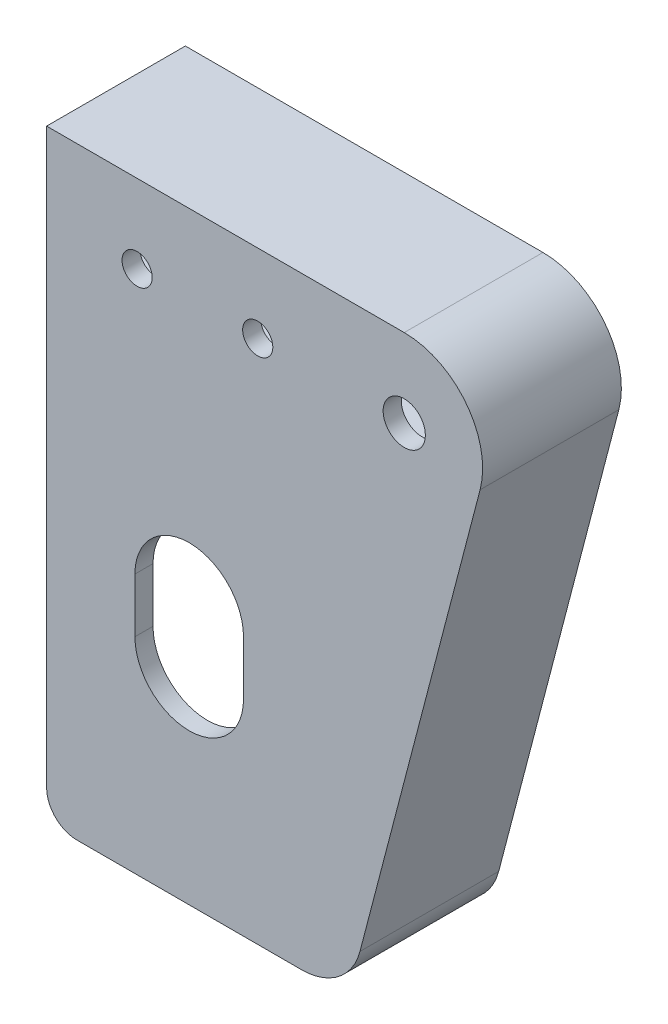
SolidWorks part; units mm, degrees
ref_plane "Front Plane" through (0, 0, 0) normal (0, 0, 1) x (1, 0, 0)
ref_plane "Top Plane" through (0, 0, 0) normal (0, 1, 0) x (1, 0, 0)
ref_plane "Right Plane" through (0, 0, 0) normal (1, 0, 0) x (0, 0, -1)
sketch "Sketch1" plane through (0, 0, 0) normal (0, 0, 1) x (1, 0, 0)
  line L1 (-35, 10) -> (24.2897, 10)
  line L2 (-35, 10) -> (-35, -16)
  line L3 (-35, -16) -> (24.2897, -16)
  line L5 (-35, 10) -> (35.2063, -10.0589) construction
  line L6 (-35, -16) -> (20.8786, 9.5445) construction
  arc A0 (24.2897, -16) -> (24.2897, 10) centre (24.2897, -3) ccw
  point P0 (0, 0)
  dimension "D1" = 26
extrude "Boss-Extrude1" add sketch "Sketch1" against normal blind 3
sketch "Sketch2" plane through (0, 0, -3) normal (0, 0, -1) x (-1, 0, 0)
  line L0 (-24.2897, 7) -> (35, 7)
  line L1 (-24.2897, -13) -> (35, -13)
  line L2 (35, 7) -> (35, 10)
  line L3 (35, -16) -> (35, 10)
  line L4 (35, 10) -> (-24.2897, 10)
  line L5 (-24.2897, -16) -> (35, -16)
  line L6 (35, -16) -> (35, -13)
  line L7 (35, 10) -> (-24.2897, 10)
  line L8 (-24.2897, -16) -> (35, -16)
  arc A0 (-24.2897, 7) -> (-24.2897, -13) centre (-24.2897, -3) ccw
  arc A1 (-24.2897, 10) -> (-24.2897, -16) centre (-24.2897, -3) ccw
  arc A2 (-24.2897, 10) -> (-24.2897, -16) centre (-24.2897, -3) ccw
  dimension "D1" = 0
  dimension "D2" = 3
extrude "Boss-Extrude2" add sketch "Sketch2" along normal blind 20
sketch "Sketch3" plane through (0, 0, 0) normal (0, 0, 1) x (1, 0, 0)
  circle A0 centre (24.2897, -3) radius 3.5
  dimension "D1" = 7
extrude "Cut-Extrude1" cut sketch "Sketch3" against normal blind 20
sketch "Sketch4" plane through (0, 0, 0) normal (0, 0, 1) x (1, 0, 0)
  line L0 (-35, 10) -> (-35, -90)
  line L1 (-35, -90) -> (15, -90)
  line L3 (-35, 10) -> (-35, -16)
  line L4 (-35, -16) -> (24.2897, -16)
  line L5 (24.2897, 10) -> (-35, 10)
  line L7 (-35, -16) -> (24.2897, -16)
  line L8 (24.2897, 10) -> (-35, 10)
  line L9 (15, -90) -> (36.8676, -6.2856)
  arc A1 (24.2897, -16) -> (24.2897, 10) centre (24.2897, -3) ccw
  arc A2 (24.2897, -16) -> (24.2897, 10) centre (24.2897, -3) ccw
  line M10 (-35, -16) -> (24.2897, -16)
  arc M11 (24.2897, -16) -> (24.2897, 10) centre (24.2897, -3) ccw
  dimension "D2" = 50
  dimension "D3" = 100
  dimension "D1" = 0
extrude "Boss-Extrude3" add sketch "Sketch4" against normal blind 3 contours L1 L9 L0 M11 M10
fillet "Fillet1" radius 10 1 edges at (15, -90, -1.5)
fillet "Fillet3" radius 5 1 edges at (-35, -90, -1.5)
sketch "Sketch5" plane through (0, 0, -3) normal (0, 0, -1) x (-1, 0, 0)
  line L8 (-31.8656, -13.5643) -> (-14.0494, -81.7692)
  line L9 (-7.2766, -87) -> (30, -87)
  line L10 (30, -87) -> (30, -90)
  line L11 (-33.965, -5.5274) -> (-14.0494, -81.7692) construction
  line L12 (-7.2766, -90) -> (30, -90)
  line L13 (35, -85) -> (35, -16)
  line L14 (35, -16) -> (-24.2897, -16)
  line L15 (-36.8676, -6.2856) -> (-16.952, -82.5274)
  line L16 (-7.2766, -90) -> (30, -90)
  line L17 (35, -85) -> (35, -16)
  line L18 (35, -16) -> (-24.2897, -16)
  line L19 (-36.8676, -6.2856) -> (-16.952, -82.5274)
  arc A6 (-14.0494, -81.7692) -> (-7.2766, -87) centre (-7.2766, -80) ccw
  arc A9 (30, -90) -> (35, -85) centre (30, -85) ccw
  arc A10 (-36.8676, -6.2856) -> (-24.2897, -16) centre (-24.2897, -3) ccw
  arc A11 (-16.952, -82.5274) -> (-7.2766, -90) centre (-7.2766, -80) ccw
  arc A12 (30, -90) -> (35, -85) centre (30, -85) ccw
  arc A13 (-36.8676, -6.2856) -> (-24.2897, -16) centre (-24.2897, -3) ccw
  arc A14 (-16.952, -82.5274) -> (-7.2766, -90) centre (-7.2766, -80) ccw
  line M12 (-7.2766, -90) -> (30, -90)
  arc M16 (-24.2897, -16) -> (-36.8676, -6.2856) centre (-24.2897, -3) cw
  line M17 (-36.8676, -6.2856) -> (-16.952, -82.5274)
  arc M18 (-16.952, -82.5274) -> (-7.2766, -90) centre (-7.2766, -80) ccw
  dimension "D1" = 0
  dimension "D2" = 3
extrude "Boss-Extrude4" add sketch "Sketch5" along normal blind 20 contours A6 L8 L10 L9 M16 M17 M18 M12
sketch "Sketch6" plane through (0, 0, -3) normal (0, 0, -1) x (-1, 0, 0)
  line L0 (11.3617, -87) -> (11.3617, -16) construction
  line L1 (-45.4177, -38) -> (42.1533, -38) construction
  line L4 (-11.8139, -65) -> (42.1533, -65) construction
  line L5 (-31.8656, -13.5643) -> (-14.0494, -81.7692)
  line L6 (-7.2766, -87) -> (30, -87)
  line L7 (30, -87) -> (30, -90)
  line L8 (35, -85) -> (35, -16)
  line L9 (35, -16) -> (-24.2897, -16)
  line L10 (-31.8656, -13.5643) -> (-14.0494, -81.7692)
  line L11 (-7.2766, -87) -> (30, -87)
  line L12 (30, -87) -> (30, -90)
  line L13 (35, -85) -> (35, -38)
  line L14 (35, -16) -> (-24.2897, -16)
  line L15 (-45.4177, -47) -> (42.1533, -47) construction
  line L16 (-11.8139, -56) -> (42.1533, -56) construction
  line L17 (11.3617, -56) -> (11.3617, -47) construction
  line L18 (2.3617, -56) -> (2.3617, -47)
  line L19 (20.3617, -56) -> (20.3617, -47)
  line L20 (26.9175, -30.7663) -> (26.9175, -70.6479) construction
  arc A2 (2.3617, -56) -> (20.3617, -56) centre (11.3617, -56) ccw
  arc A3 (-31.8656, -13.5643) -> (-24.2897, -16) centre (-24.2897, -3) ccw
  arc A4 (-14.0494, -81.7692) -> (-7.2766, -87) centre (-7.2766, -80) ccw
  arc A5 (30, -90) -> (35, -85) centre (30, -85) ccw
  arc A6 (-31.8656, -13.5643) -> (-24.2897, -16) centre (-24.2897, -3) ccw
  arc A7 (-14.0494, -81.7692) -> (-7.2766, -87) centre (-7.2766, -80) ccw
  arc A8 (30, -90) -> (35, -85) centre (30, -85) ccw
  arc A9 (20.3617, -47) -> (2.3617, -47) centre (11.3617, -47) ccw
  point P23 (11.3617, -51.5)
  dimension "D2" = 22
  dimension "D6" = 9
  dimension "D3" = 9
  dimension "D4" = 22
  dimension "D1" = 0
  dimension "D5" = 9
sketch "Sketch7" plane through (0, 0, -3) normal (0, 0, -1) x (-1, 0, 0)
  line L0 (-29.8867, -3) -> (35, -3) construction
  line L3 (35, 7) -> (-24.2897, 7)
  line L4 (-24.2897, -13) -> (35, -13)
  line L5 (35, -13) -> (35, 7)
  line L6 (35, 7) -> (-24.2897, 7)
  line L7 (-24.2897, -13) -> (35, -13)
  line L8 (35, -3) -> (35, 7)
  circle A0 centre (0, -3) radius 2.5
  arc A1 (-24.2897, 7) -> (-24.2897, -13) centre (-24.2897, -3) ccw
  arc A2 (-24.2897, 7) -> (-24.2897, -13) centre (-24.2897, -3) ccw
  circle A3 centre (20, -3) radius 2.5
  dimension "D4" = 5
  dimension "D2" = 15
  dimension "D3" = 20
  dimension "D1" = 0
extrude "Cut-Extrude2" cut sketch "Sketch7" against normal blind 20 contours L0 A0 | A0 L0 | A3 L0 | L0 A3
extrude "Cut-Extrude4" cut sketch "Sketch6" against normal blind 20 contours L19 A9 L18 A2
